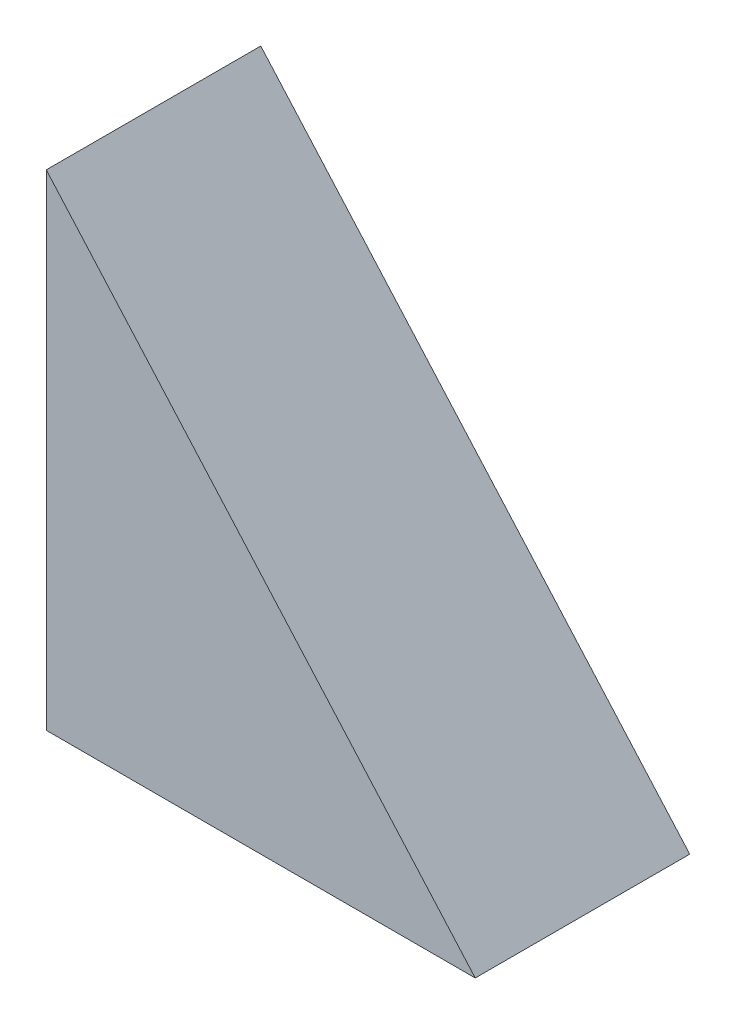
SolidWorks part; units mm, degrees
ref_plane "Front Plane" through (0, 0, 0) normal (0, 0, 1) x (1, 0, 0)
ref_plane "Top Plane" through (0, 0, 0) normal (0, 1, 0) x (1, 0, 0)
ref_plane "Right Plane" through (0, 0, 0) normal (1, 0, 0) x (0, 0, -1)
sketch "Sketch1" plane through (0, 0, 0) normal (0, 0, 1) x (1, 0, 0)
  line L0 (0, 0) -> (9.652, 0)
  line L1 (9.652, 0) -> (0, 10.922)
  line L2 (0, 10.922) -> (0, 0)
  dimension "D1" = 10.922
  dimension "D2" = 9.652
extrude "Boss-Extrude1" add sketch "Sketch1" along normal blind 4.826
